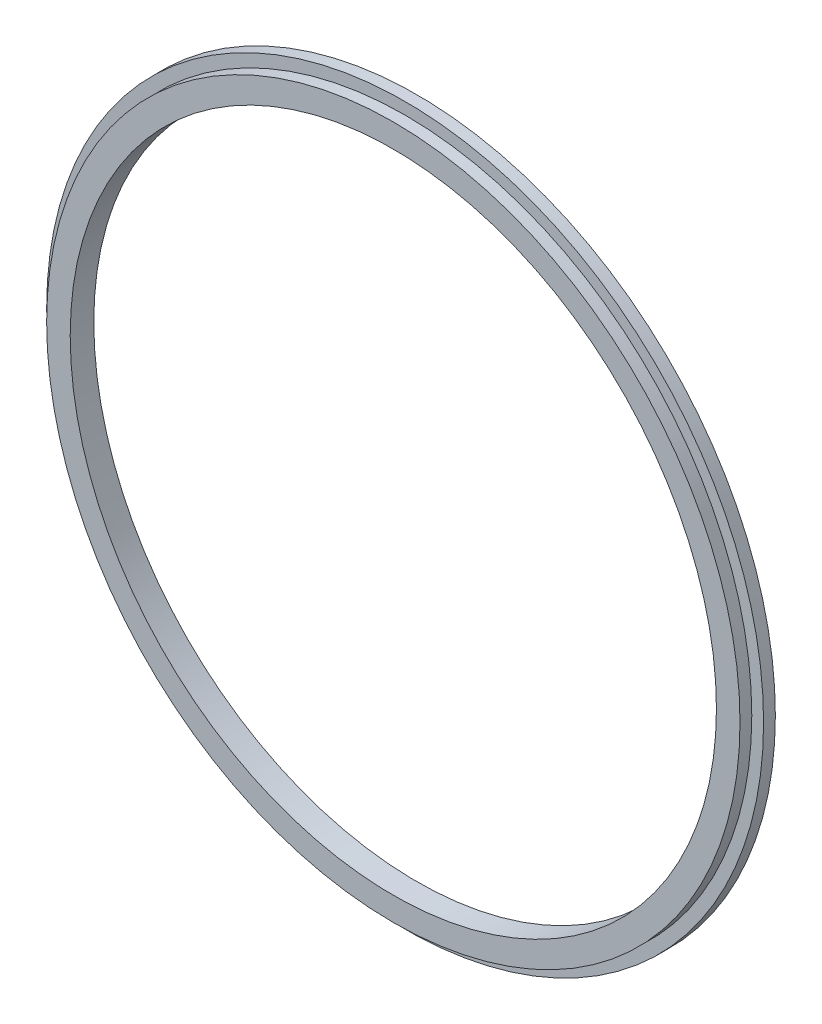
SolidWorks part; units mm, degrees
ref_plane "Front Plane" through (0, 0, 0) normal (0, 0, 1) x (1, 0, 0)
ref_plane "Top Plane" through (0, 0, 0) normal (0, 1, 0) x (1, 0, 0)
ref_plane "Right Plane" through (0, 0, 0) normal (1, 0, 0) x (0, 0, -1)
sketch "Sketch1" plane through (0, 0, 0) normal (0, 0, 1) x (1, 0, 0)
  circle A0 centre (0, 0) radius 58.829
  circle A1 centre (0, 0) radius 54.829
  dimension "D1" = 117.658
  dimension "D2" = 4
extrude "Boss-Extrude1" add sketch "Sketch1" along normal blind 2
sketch "Sketch3" plane through (0, 0, 0) normal (0, 0, -1) x (-1, 0, 0)
  circle A0 centre (0, 0) radius 54.829 construction
  circle A1 centre (0, 0) radius 54.829
  circle A2 centre (0, 0) radius 60.829
  circle A3 centre (0, 0) radius 58.829 construction
  dimension "D1" = 2
extrude "Boss-Extrude2" add sketch "Sketch3" along normal blind 2
